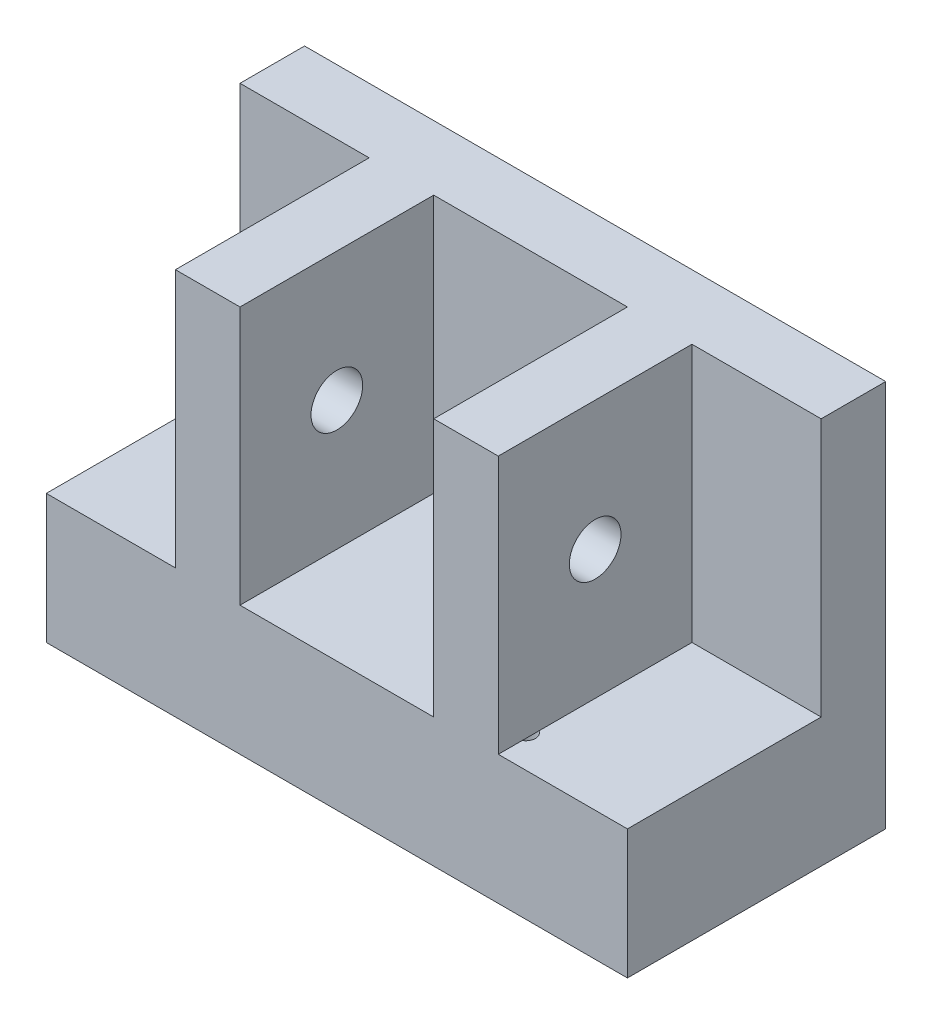
SolidWorks part; units mm, degrees
ref_plane "Front Plane" through (0, 0, 0) normal (0, 0, 1) x (1, 0, 0)
ref_plane "Top Plane" through (0, 0, 0) normal (0, 1, 0) x (1, 0, 0)
ref_plane "Right Plane" through (0, 0, 0) normal (1, 0, 0) x (0, 0, -1)
sketch "Sketch3" plane through (0, 0, 0) normal (0, 1, 0) x (1, 0, 0)
  line L0 (-25, 0) -> (-15, 0)
  line L1 (-15, 0) -> (-15, 30)
  line L2 (-15, 30) -> (15, 30)
  line L3 (15, 30) -> (15, 0)
  line L4 (15, 0) -> (25, 0)
  line L5 (25, 0) -> (25, 40)
  line L6 (25, 40) -> (-25, 40)
  line L7 (-25, 40) -> (-25, 0)
  line L8 (25, 30) -> (45, 30)
  line L9 (45, 30) -> (45, 40)
  line L10 (45, 40) -> (25, 40)
  line L11 (0, 40) -> (0, 30) construction
  line L12 (-45, 40) -> (-25, 40)
  line L13 (-45, 30) -> (-45, 40)
  line L14 (-25, 30) -> (-45, 30)
  point P8 (0, 30)
  dimension "D1" = 40
  dimension "D2" = 10
  dimension "D3" = 30
  dimension "D4" = 10
  dimension "D5" = 20
extrude "Boss-Extrude1" add sketch "Sketch3" along normal blind 40 contours L14 L7 L12 L13 | L11 L6 L7 L0 L1 L2 | L6 L11 L2 L3 L4 L5 | L9 L10 L5 L8
sketch "Sketch4" plane through (-15, 0, 0) normal (1, 0, 0) x (0, 0, -1)
  line L1 (0, 40) -> (0, 0) construction
  line L2 (0, 0) -> (30, 0) construction
  circle A0 centre (15, 20) radius 4
  point P5 (15, 15)
  point P9 (0, 20)
  point P11 (15, 0)
  dimension "D1" = 8
extrude "Cut-Extrude1" cut sketch "Sketch4" against normal through all both and the other way through all
sketch "Sketch7" plane through (0, 0, 0) normal (0, -1, 0) x (1, 0, 0)
  line L0 (45, -30) -> (45, -40) construction
  line L1 (-45, -40) -> (45, -40)
  line L2 (-45, -40) -> (-45, 0)
  line L3 (-45, 0) -> (45, 0)
  line L4 (45, -40) -> (45, 0)
  line L5 (15, 0) -> (25, 0) construction
extrude "Boss-Extrude3" add sketch "Sketch7" along normal blind 20
sketch "Sketch8" plane through (0, -20, 0) normal (0, -1, 0) x (1, 0, 0)
  line L0 (0, 0) -> (0, -40) construction
  line L1 (45, 0) -> (-45, 0) construction
  line L2 (-45, -40) -> (45, -40) construction
  circle A0 centre (-24.25, -5) radius 1.5
  circle A1 centre (24.25, -5) radius 1.5
  dimension "D1" = 3
  dimension "D2" = 48.5
  dimension "D3" = 35
extrude "Cut-Extrude3" cut sketch "Sketch8" against normal blind 20
equation "\"D4@Sketch3\"=\"D2@Sketch3\""
